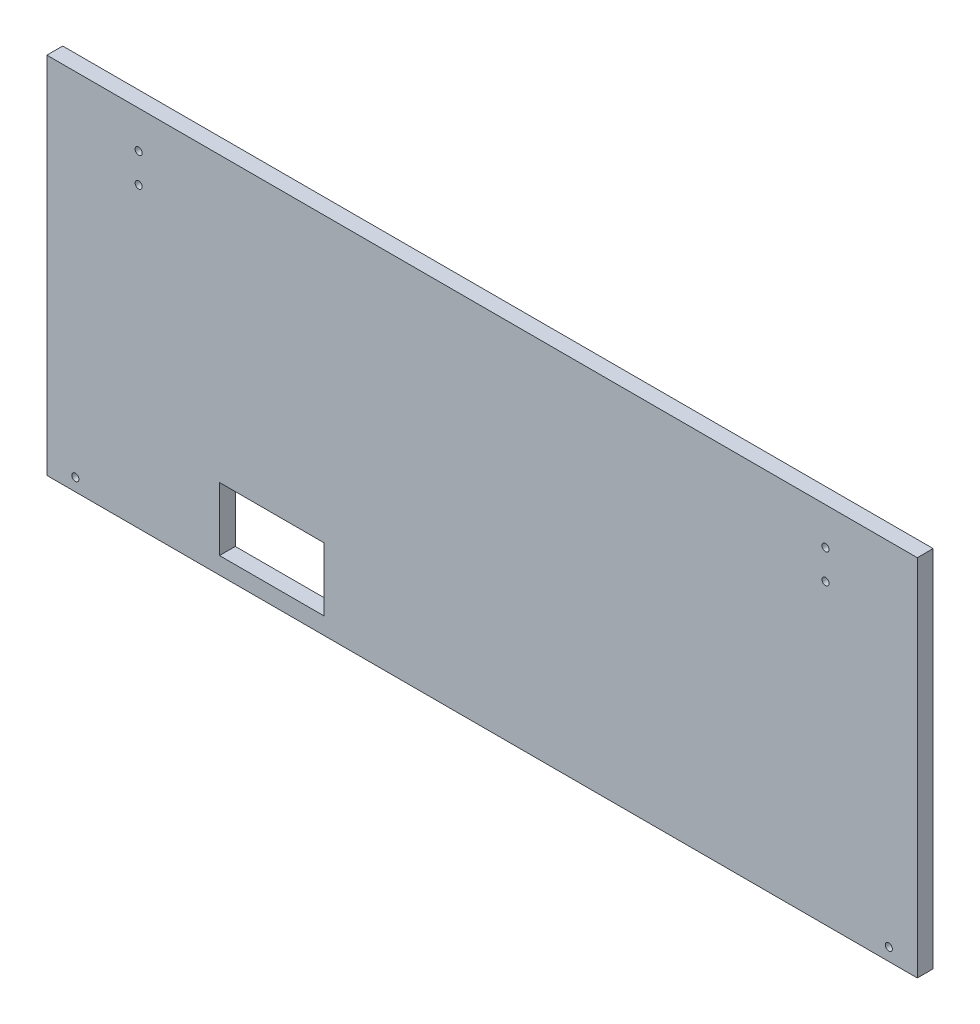
SolidWorks part; units mm, degrees
material "Multistrato di pioppo"
ref_plane "Piano frontale" through (0, 0, 0) normal (0, 0, 1) x (1, 0, 0)
ref_plane "Piano superiore" through (0, 0, 0) normal (0, 1, 0) x (1, 0, 0)
ref_plane "Piano destro" through (0, 0, 0) normal (1, 0, 0) x (0, 0, -1)
sketch "Schizzo1" plane through (0, 0, 0) normal (0, 0, 1) x (1, 0, 0)
  line L1 (275, -115) -> (-275, -115)
  line L2 (275, -115) -> (275, 115)
  line L3 (275, 115) -> (-275, 115)
  line L4 (-275, -115) -> (-275, 115)
  line L5 (275, -115) -> (-275, 115) construction
  line L6 (275, 115) -> (-275, -115) construction
  point P4 (0, 0)
  dimension "D1" = 230
  dimension "D2" = 550
extrude "Estrusione-Estrusione1" add sketch "Schizzo1" along normal blind 10
sketch "Schizzo2" plane through (0, 0, 0) normal (0, 0, -1) x (-1, 0, 0)
  line L0 (275, -115) -> (-275, -115) construction
  line L1 (99.9257, -104.3) -> (165.9257, -104.3)
  line L2 (99.9257, -104.3) -> (99.9257, -64.3)
  line L3 (99.9257, -64.3) -> (165.9257, -64.3)
  line L4 (165.9257, -104.3) -> (165.9257, -64.3)
  line L5 (275, 115) -> (275, -115) construction
  line L6 (-275, -115) -> (-275, 115) construction
  circle A0 centre (-217, 91.5) radius 2.25
  circle A1 centre (-217, 73) radius 2.25
  circle A2 centre (217, 91.5) radius 2.25
  circle A3 centre (217, 73) radius 2.25
  circle A4 centre (-257, -107) radius 2.25
  circle A5 centre (257, -107) radius 2.25
  dimension "D1" = 4.5
  dimension "D2" = 10.7
  dimension "D3" = 66
  dimension "D4" = 109.0743
  dimension "D5" = 40
  dimension "D6" = 18
  dimension "D7" = 8
  dimension "D8" = 18
  dimension "D9" = 8
extrude "Taglio-Estrusione1" cut sketch "Schizzo2" against normal blind 10
